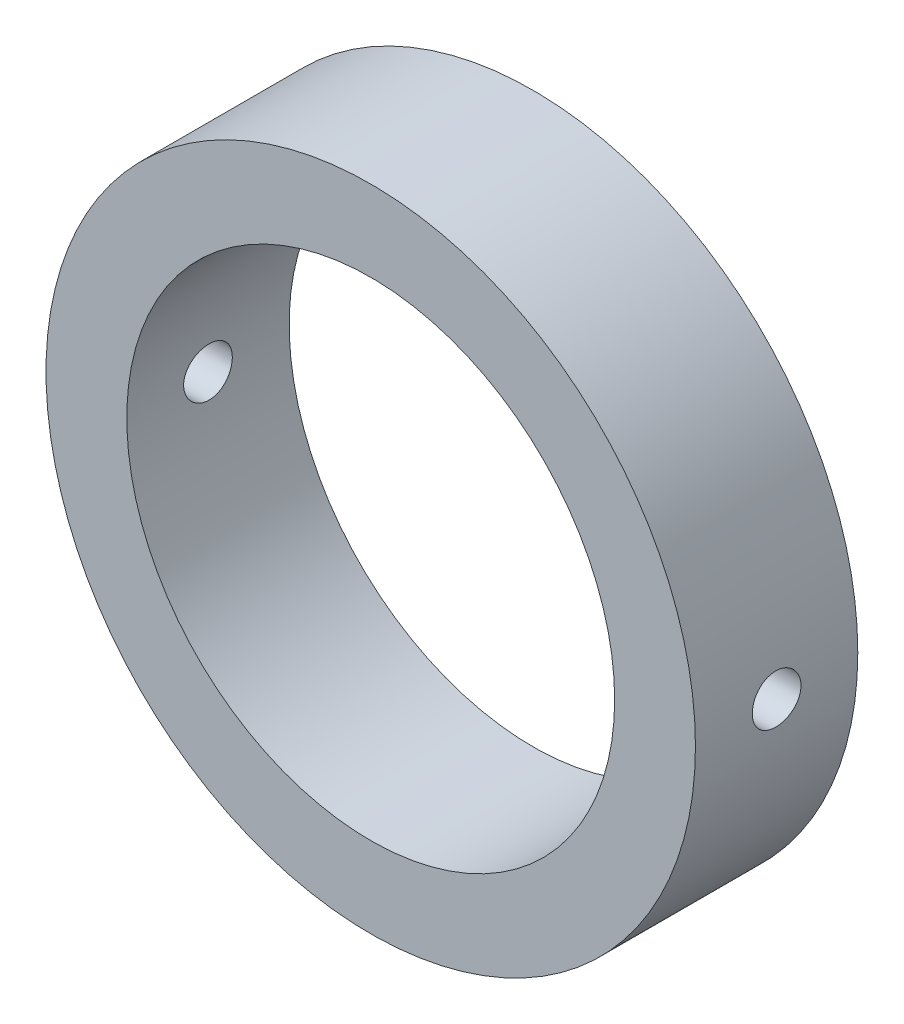
SolidWorks part; units mm, degrees
ref_plane "Front Plane" through (0, 0, 0) normal (0, 0, 1) x (1, 0, 0)
ref_plane "Top Plane" through (0, 0, 0) normal (0, 1, 0) x (1, 0, 0)
ref_plane "Right Plane" through (0, 0, 0) normal (1, 0, 0) x (0, 0, -1)
sketch "Sketch1" plane through (0, 0, 0) normal (0, 0, 1) x (1, 0, 0)
  circle A0 centre (0, 0) radius 15.025
  circle A1 centre (0, 0) radius 20
  dimension "D1" = 30.05
  dimension "D2" = 40
extrude "Boss-Extrude1" add sketch "Sketch1" along normal blind 10
sketch "Sketch2" plane through (0, 0, 0) normal (1, 0, 0) x (0, 0, -1)
  line L0 (-5, 20) -> (-5, -20) construction
  line L1 (0, 20) -> (-10, 20) construction
  line L2 (-10, -20) -> (0, -20) construction
  circle A0 centre (-5, 0) radius 1.5
  dimension "D1" = 3
extrude "Cut-Extrude1" cut sketch "Sketch2" against normal through all both and the other way through all
